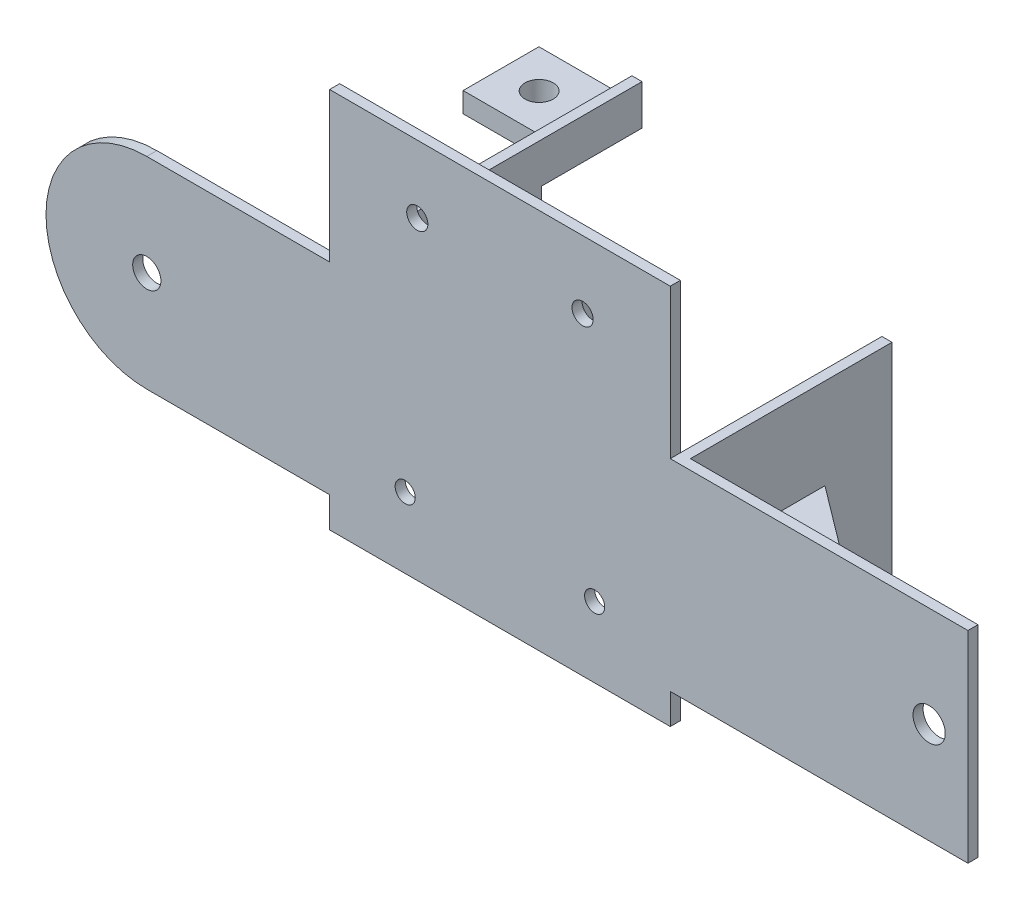
SolidWorks part; units mm, degrees
ref_plane "Alzado" through (0, 0, 0) normal (0, 0, 1) x (1, 0, 0)
ref_plane "Planta" through (0, 0, 0) normal (0, 1, 0) x (1, 0, 0)
ref_plane "Vista lateral" through (0, 0, 0) normal (1, 0, 0) x (0, 0, -1)
sketch "Croquis1" plane through (0, 0, 0) normal (0, 0, 1) x (1, 0, 0)
  line L1 (232.1668, -404.8957) -> (84.5, -404.8957)
  line L2 (232.1668, -404.8957) -> (232.1668, -504.8957)
  line L3 (232.1668, -504.8957) -> (84.5, -504.8957)
  line L4 (-84.5, -504.8957) -> (-175.1905, -504.8957)
  line L5 (-84.5, -520) -> (84.5, -520)
  line L6 (-84.5, -520) -> (-84.5, -504.8957)
  line L7 (-84.5, -330.7877) -> (84.5, -330.7877)
  line L8 (84.5, -520) -> (84.5, -504.8957)
  line L9 (84.5, -520) -> (84.5, 0) construction
  line L10 (-84.5, -404.8957) -> (-84.5, -330.7877)
  line L11 (-84.5, -404.8957) -> (-175.1905, -404.8957)
  line L12 (84.5, -404.8957) -> (84.5, -330.7877)
  circle A0 centre (41, -364.3) radius 5.25 construction
  arc A1 (-175.1905, -404.8957) -> (-175.1905, -504.8957) centre (-175.1905, -454.8957) ccw
  circle A2 centre (-175.1905, -454.8957) radius 7
  circle A3 centre (-41, -364.3) radius 5.25 construction
  circle A4 centre (47, -485) radius 5 construction
  circle A5 centre (-47, -485) radius 5 construction
  circle A6 centre (41, -364.3) radius 5.25
  circle A7 centre (-41, -364.3) radius 5.25
  circle A8 centre (47, -485) radius 5
  circle A9 centre (-47, -485) radius 5
  circle A10 centre (212.9229, -454.7662) radius 8
  dimension "D1" = 100
  dimension "D2" = 407.3573
  dimension "D3" = 189.2123
  dimension "D4" = 169
extrude "Saliente-Extruir1" add sketch "Croquis1" along normal blind 5 contours L11 A1 L4 L6 L5 L8 L3 L2 L1 L12 L7 L10 A9 A8 A7 A6 A2
sketch "Croquis2" plane through (0, 0, 0) normal (0, 0, -1) x (-1, 0, 0)
  line L1 (-84.5, -404.8957) -> (-89.5, -404.8957)
  line L2 (-84.5, -404.8957) -> (-84.5, -504.8957)
  line L3 (-84.5, -504.8957) -> (-89.5, -504.8957)
  line L4 (-89.5, -404.8957) -> (-89.5, -504.8957)
  line L5 (-232.1668, -504.8957) -> (-84.5, -504.8957) construction
  line L7 (84.5, -504.8957) -> (89.5, -504.8957)
  line L8 (84.5, -504.8957) -> (84.5, -404.8957)
  line L9 (84.5, -404.8957) -> (89.5, -404.8957)
  line L10 (89.5, -504.8957) -> (89.5, -404.8957)
  line L11 (84.5, -404.8957) -> (175.1905, -404.8957) construction
  dimension "D1" = 100
  dimension "D2" = 5
  dimension "D3" = 100
  dimension "D4" = 5
extrude "Saliente-Extruir2" add sketch "Croquis2" along normal blind 100
sketch "Croquis3" plane through (0, 0, -100) normal (0, 0, -1) x (-1, 0, 0)
  line L1 (84.5, -504.8957) -> (89.5, -504.8957)
  line L2 (84.5, -504.8957) -> (84.5, -484.8957)
  line L3 (84.5, -484.8957) -> (89.5, -484.8957)
  line L4 (89.5, -504.8957) -> (89.5, -484.8957)
  line L5 (89.5, -504.8957) -> (89.5, -404.8957) construction
  line L7 (89.5, -404.8957) -> (84.5, -404.8957)
  line L8 (89.5, -404.8957) -> (89.5, -424.8957)
  line L9 (89.5, -424.8957) -> (84.5, -424.8957)
  line L10 (84.5, -404.8957) -> (84.5, -424.8957)
  line L11 (84.5, -404.8957) -> (84.5, -504.8957) construction
  dimension "D1" = 20
  dimension "D2" = 5
  dimension "D3" = 20
  dimension "D4" = 5
extrude "Saliente-Extruir3" add sketch "Croquis3" along normal blind 50
sketch "Croquis4" plane through (-89.5, 0, 0) normal (-1, 0, 0) x (0, 0, 1)
  line L1 (-143.8446, -409.35) -> (-106.2262, -409.35)
  line L2 (-143.8446, -409.35) -> (-143.8446, -419.35)
  line L3 (-143.8446, -419.35) -> (-106.2262, -419.35)
  line L4 (-106.2262, -409.35) -> (-106.2262, -419.35)
  line L5 (-143.8446, -500.3774) -> (-106.2262, -500.3774)
  line L6 (-143.8446, -500.3774) -> (-143.8446, -490.3774)
  line L7 (-143.8446, -490.3774) -> (-106.2262, -490.3774)
  line L8 (-106.2262, -500.3774) -> (-106.2262, -490.3774)
  dimension "D1" = 10
  dimension "D2" = 37.6184
  dimension "D3" = 10
  dimension "D4" = 37.6184
extrude "Saliente-Extruir4" add sketch "Croquis4" along normal blind 40
sketch "Croquis5" plane through (0, -500.3774, 0) normal (0, -1, 0) x (1, 0, 0)
  circle A0 centre (-110.4528, -124.8866) radius 7
extrude "Cortar-Extruir1" cut sketch "Croquis5" against normal through all
ref_plane "Plano1" through (0, -454.8957, 0) normal (0, -1, 0) x (-1, 0, 0)
sketch "Croquis6" plane through (0, -454.8957, 0) normal (0, -1, 0) x (-1, 0, 0)
  line L0 (89.5, 75) -> (144.9789, 0)
  line L1 (89.5, 150) -> (89.5, 0) construction
  line L2 (89.5, 0) -> (175.1905, 0) construction
  point P6 (144.9789, 0)
  point P7 (89.5, 75)
rib "Nervio1" sketch "Croquis6" sketch "Croquis6" thickness 10 extrusion direction parallel to sketch draft on no parameters "D1"=10
sketch "Croquis7" plane through (0, -454.8957, 0) normal (0, -1, 0) x (-1, 0, 0)
  line L0 (-178.0975, 0) -> (-89.5, 66.74)
  line L1 (-232.1668, 0) -> (-89.5, 0) construction
  line L2 (-89.5, 100) -> (-89.5, 0) construction
rib "Nervio2" sketch "Croquis7" sketch "Croquis7" thickness 10 extrusion direction parallel to sketch draft on no parameters "D1"=10
